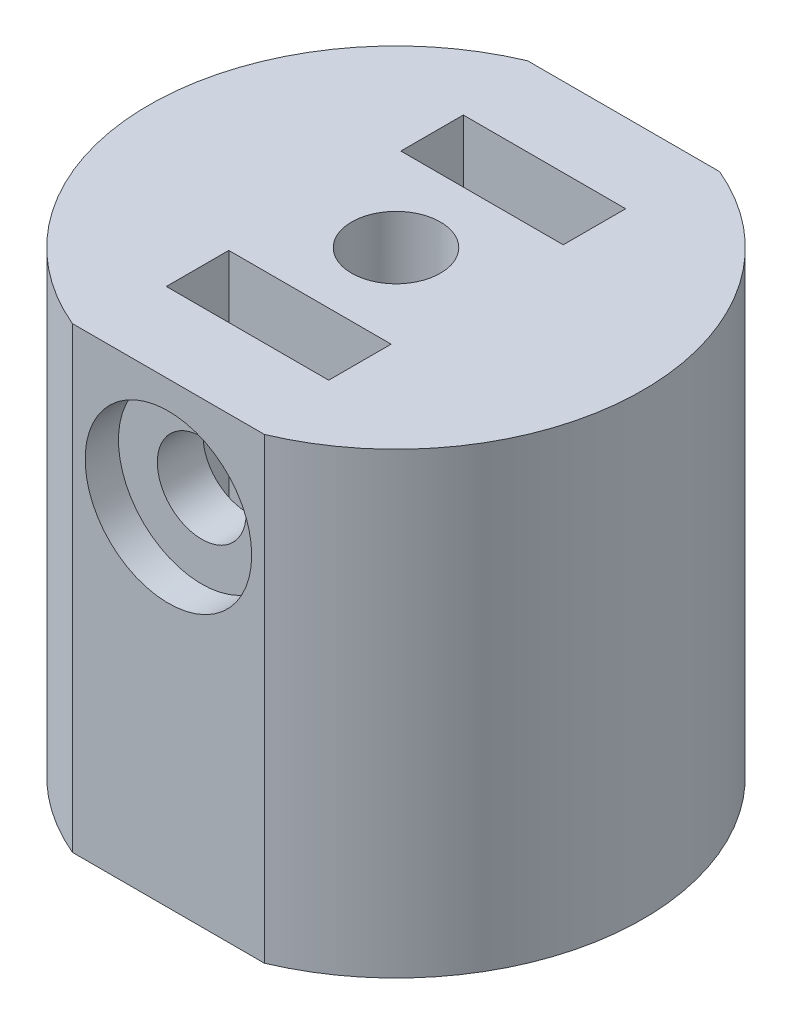
SolidWorks part; units mm, degrees
ref_plane "Plan de face" through (0, 0, 0) normal (0, 0, 1) x (1, 0, 0)
ref_plane "Plan de dessus" through (0, 0, 0) normal (0, 1, 0) x (1, 0, 0)
ref_plane "Plan de droite" through (0, 0, 0) normal (1, 0, 0) x (0, 0, -1)
sketch "Esquisse1" plane through (0, 0, 0) normal (0, 1, 0) x (1, 0, 0)
  circle A0 centre (0, 0) radius 11.3
  dimension "D1" = 22.6
extrude "Boss.-Extru.1" add sketch "Esquisse1" along normal blind 16.5
sketch "Esquisse2" plane through (0, 0, 0) normal (0, -1, 0) x (1, 0, 0)
  circle A0 centre (0, 0) radius 4.7
  dimension "D1" = 9.4
extrude "Enlèv. mat.-Extru.1" cut sketch "Esquisse2" against normal blind 1.5
sketch "Esquisse3" plane through (0, 1.5, 0) normal (0, -1, 0) x (1, 0, 0)
  circle A0 centre (0, 0) radius 2.6
  dimension "D1" = 5.2
extrude "Enlèv. mat.-Extru.2" cut sketch "Esquisse3" against normal blind 3
sketch "Esquisse4" plane through (0, 4.5, 0) normal (0, -1, 0) x (1, 0, 0)
  line L0 (-2.0094, 1.65) -> (2.0094, 1.65)
  line L1 (-2.0094, -1.65) -> (2.0094, -1.65)
  line L2 (9.075, 0) -> (-9.075, 0) construction
  circle A0 centre (0, 0) radius 2.6
  circle M3 centre (0, 0) radius 2.6
  dimension "D2" = 5.2
  dimension "D1" = 3.3
extrude "Enlèv. mat.-Extru.3" cut sketch "Esquisse4" against normal blind 6 contours L1 L0 M3
sketch "Esquisse5" plane through (0, 16.5, 0) normal (0, 1, 0) x (1, 0, 0)
  circle A0 centre (0, 0) radius 1.6
  dimension "D1" = 3.2
extrude "Enlèv. mat.-Extru.4" cut sketch "Esquisse5" against normal blind 6.5
sketch "Esquisse6" plane through (0, 16.5, 0) normal (0, 1, 0) x (1, 0, 0)
  line L1 (-2.925, -3.1) -> (2.925, -3.1)
  line L2 (-2.925, -3.1) -> (-2.925, -5.35)
  line L3 (-2.925, -5.35) -> (2.925, -5.35)
  line L4 (2.925, -3.1) -> (2.925, -5.35)
  point P4 (0, -3.1)
  dimension "D1" = 2.25
  dimension "D2" = 3.1
  dimension "D3" = 5.85
extrude "Enlèv. mat.-Extru.5" cut sketch "Esquisse6" against normal blind 8
sketch "Esquisse7" plane through (0, 0, 3.1) normal (0, 0, 1) x (1, 0, 0)
  line L0 (11.3, 16.5) -> (-11.3, 16.5) construction
  circle A0 centre (0, 12.5) radius 1.6
  dimension "D1" = 3.2
  dimension "D2" = 4
extrude "Enlèv. mat.-Extru.6" cut sketch "Esquisse7" against normal blind 3.1 and the other way through all
sketch "Esquisse8" plane through (0, 16.5, 0) normal (0, 1, 0) x (1, 0, 0)
  line L0 (-3.4598, -8.2) -> (3.4598, -8.2)
  line L1 (-2.925, -5.35) -> (2.925, -5.35) construction
  line L2 (-2.925, -5.35) -> (2.925, -5.35) construction
  line L3 (3.4598, 8.2) -> (-3.4598, 8.2)
  arc A0 (3.4598, -8.2) -> (3.4598, 8.2) centre (0, 0) ccw
  circle A1 centre (0, 0) radius 11.3
  arc A2 (-3.4598, 8.2) -> (-3.4598, -8.2) centre (0, 0) ccw
  dimension "D2" = 17.8
  dimension "D3" = 22.6
  dimension "D1" = 2.85
extrude "Enlèv. mat.-Extru.7" cut sketch "Esquisse8" against normal through all
sketch "Esquisse9" plane through (0, 0, 8.2) normal (0, 0, 1) x (1, 0, 0)
  circle A0 centre (0, 12.5) radius 3
  dimension "D1" = 6
extrude "Enlèv. mat.-Extru.8" cut sketch "Esquisse9" against normal blind 1.2
mirror "Symétrie1" about plane through (0, 0, 0) normal (0, 0, 1) of "Enlèv. mat.-Extru.8", "Enlèv. mat.-Extru.6", "Enlèv. mat.-Extru.5"
